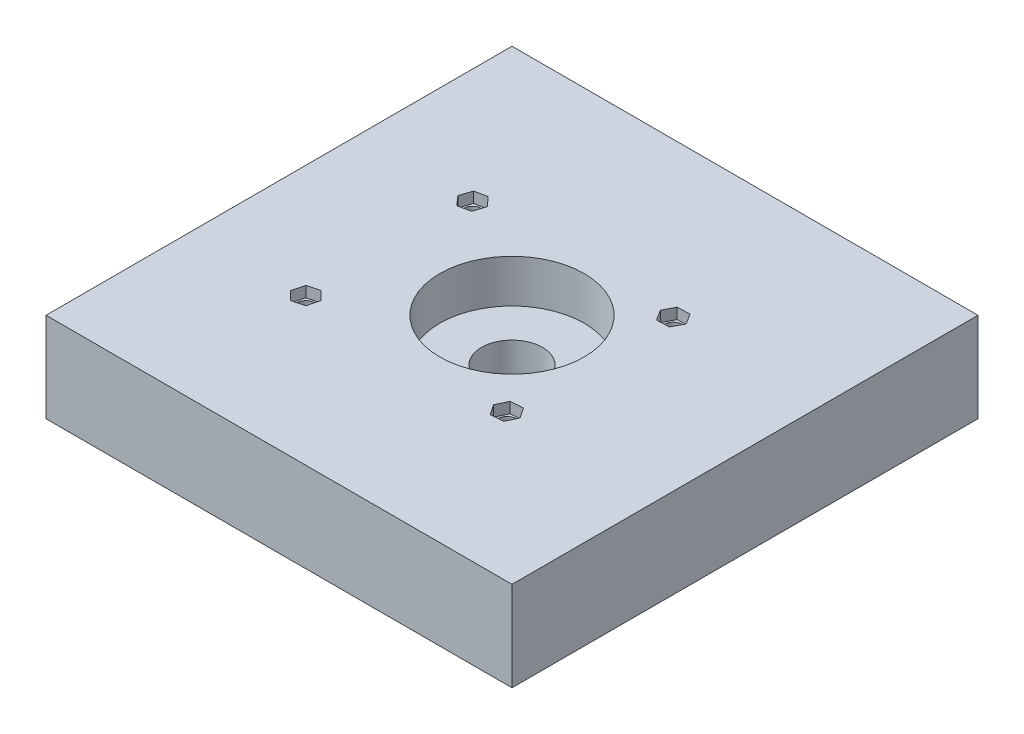
SolidWorks part; units mm, degrees
ref_plane "Front Plane" through (0, 0, 0) normal (0, 0, 1) x (1, 0, 0)
ref_plane "Top Plane" through (0, 0, 0) normal (0, 1, 0) x (1, 0, 0)
ref_plane "Right Plane" through (0, 0, 0) normal (1, 0, 0) x (0, 0, -1)
sketch "Sketch1" plane through (0, 0, 0) normal (0, 1, 0) x (1, 0, 0)
  line L1 (-65, 65) -> (65, 65)
  line L2 (-65, 65) -> (-65, -65)
  line L3 (-65, -65) -> (65, -65)
  line L4 (65, 65) -> (65, -65)
  line L5 (-65, 65) -> (65, -65) construction
  line L6 (-65, -65) -> (65, 65) construction
  point P0 (0, 0)
  dimension "D1" = 130
  dimension "D2" = 130
extrude "Boss-Extrude1" add sketch "Sketch1" along normal blind 25
sketch "Sketch2" plane through (0, 25, 0) normal (0, 1, 0) x (1, 0, 0)
  circle A0 centre (0, 0) radius 20.15
  dimension "D1" = 40.3
extrude "Cut-Extrude1" cut sketch "Sketch2" against normal blind 12
sketch "Sketch3" plane through (0, 13, 0) normal (0, 1, 0) x (1, 0, 0)
  circle A0 centre (0, 0) radius 8.5
  dimension "D1" = 17
extrude "Cut-Extrude2" cut sketch "Sketch3" against normal blind 22
sketch "Sketch5" plane through (0, 0, 0) normal (0, -1, 0) x (-1, 0, 0)
  line L0 (-65, -65) -> (-65, 65) construction
  line L1 (65, -65) -> (-65, -65) construction
  line L2 (65, 65) -> (65, -65) construction
  circle A0 centre (-22.49, -23.94) radius 2.5
  circle A1 centre (33.51, -23.9879) radius 2.5
  circle A2 centre (33.07, 22.06) radius 2.5
  circle A3 centre (-22.93, 22.0579) radius 2.5
  dimension "D3" = 5
  dimension "D4" = 5
  dimension "D6" = 5
  dimension "D8" = 5
  dimension "D1" = 42.51
  dimension "D2" = 41.06
  dimension "D5" = 56
  dimension "D7" = 46.05
  dimension "D9" = 56
  dimension "D10" = 46
  dimension "D11" = 31.93
extrude "Cut-Extrude4" cut sketch "Sketch5" against normal blind 30
sketch "Sketch7" plane through (0, 25, 0) normal (0, 1, 0) x (1, 0, 0)
  line L1 (23.9846, -20.8149) -> (20.5309, -21.0831)
  line L2 (20.5309, -21.0831) -> (19.0363, -24.2082)
  line L3 (19.0363, -24.2082) -> (20.9954, -27.0651)
  line L4 (20.9954, -27.0651) -> (24.4491, -26.7969)
  line L5 (24.4491, -26.7969) -> (25.9437, -23.6718)
  line L6 (25.9437, -23.6718) -> (23.9846, -20.8149)
  line L7 (-32.6263, -20.6384) -> (-35.9689, -21.5478)
  line L8 (-35.9689, -21.5478) -> (-36.8526, -24.8973)
  line L9 (-36.8526, -24.8973) -> (-34.3937, -27.3374)
  line L10 (-34.3937, -27.3374) -> (-31.0511, -26.428)
  line L11 (-31.0511, -26.428) -> (-30.1674, -23.0785)
  line L12 (-30.1674, -23.0785) -> (-32.6263, -20.6384)
  line L13 (-34.1479, 18.7679) -> (-30.7579, 19.4804)
  line L14 (-30.7579, 19.4804) -> (-29.68, 22.7726)
  line L15 (-29.68, 22.7726) -> (-31.9921, 25.3521)
  line L16 (-31.9921, 25.3521) -> (-35.3821, 24.6396)
  line L17 (-35.3821, 24.6396) -> (-36.46, 21.3474)
  line L18 (-36.46, 21.3474) -> (-34.1479, 18.7679)
  line L19 (24.7794, 19.1288) -> (26.3914, 22.195)
  line L20 (26.3914, 22.195) -> (24.542, 25.1241)
  line L21 (24.542, 25.1241) -> (21.0806, 24.987)
  line L22 (21.0806, 24.987) -> (19.4686, 21.9208)
  line L23 (19.4686, 21.9208) -> (21.318, 18.9917)
  line L24 (21.318, 18.9917) -> (24.7794, 19.1288)
  circle A0 centre (22.49, -23.94) radius 3 construction
  circle A1 centre (-33.51, -23.9879) radius 3 construction
  circle A2 centre (-33.07, 22.06) radius 3 construction
  circle A3 centre (22.93, 22.0579) radius 3 construction
  dimension "D1" = 6
extrude "Cut-Extrude7" cut sketch "Sketch7" against normal blind 3
